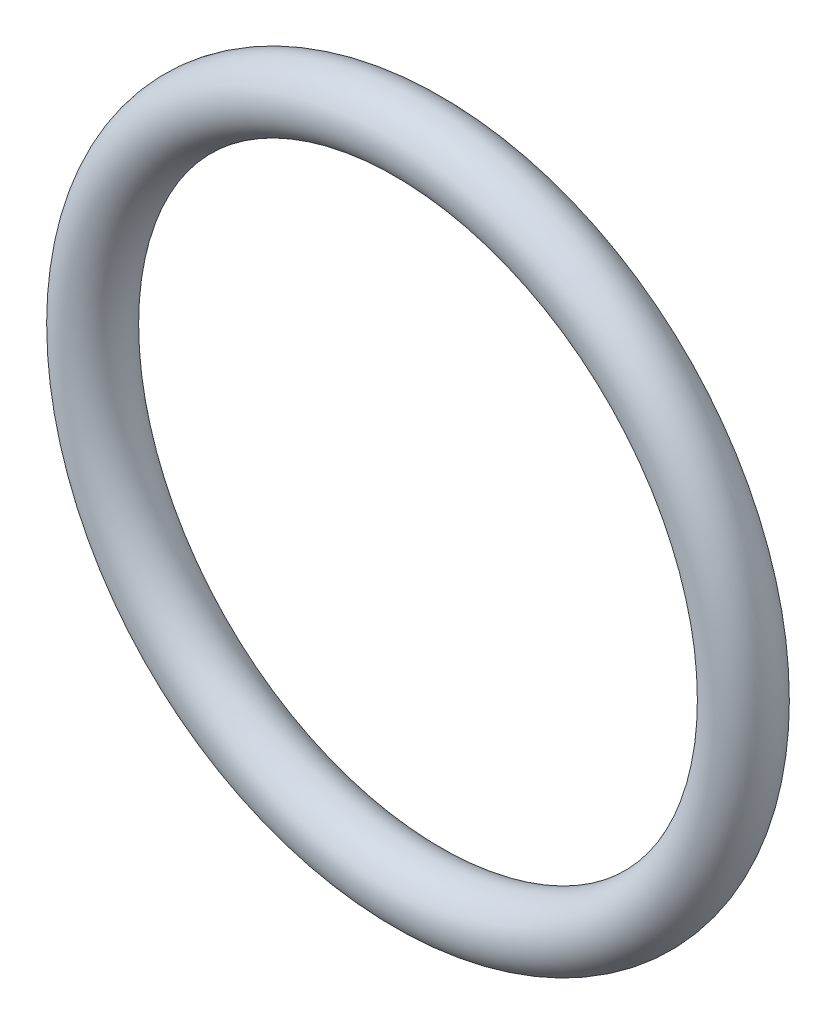
SolidWorks part; units mm, degrees
ref_plane "Front Plane" through (0, 0, 0) normal (0, 0, 1) x (1, 0, 0)
ref_plane "Top Plane" through (0, 0, 0) normal (0, 1, 0) x (1, 0, 0)
ref_plane "Right Plane" through (0, 0, 0) normal (1, 0, 0) x (0, 0, -1)
sketch "Sketch1" plane through (0, 0, 0) normal (0, 0, 1) x (1, 0, 0)
  line L0 (-5.5, 0) -> (5.5, 0) construction
  circle A0 centre (0, 0) radius 5.5
  circle A1 centre (0, 0) radius 4.5
  point P4 (4.5, 0)
  point P5 (5.5, 0)
  point P8 (0, 0)
  dimension "ID" = 9
  dimension "Width" = 1
  dimension "OD" = 11
sketch "Sketch2" plane through (0, 0, 0) normal (0, 1, 0) x (1, 0, 0)
  line L0 (-5.5, 0) -> (5.5, 0) construction
  line L1 (0, 0.5) -> (0, -0.5) construction
  circle A0 centre (5, 0) radius 0.5
  point P8 (0, 0)
  point P11 (5, 0.5)
revolve "Revolve1" add sketch "Sketch2" angle 360 about L1
sketch "Sketch3" plane through (0, 0, 0) normal (1, 0, 0) x (0, 0, -1)
  line L0 (-0.5, 0) -> (0.5, 0) construction
  line L1 (0.5, -5) -> (0.5, 5) construction
  point P2 (0, 0)
